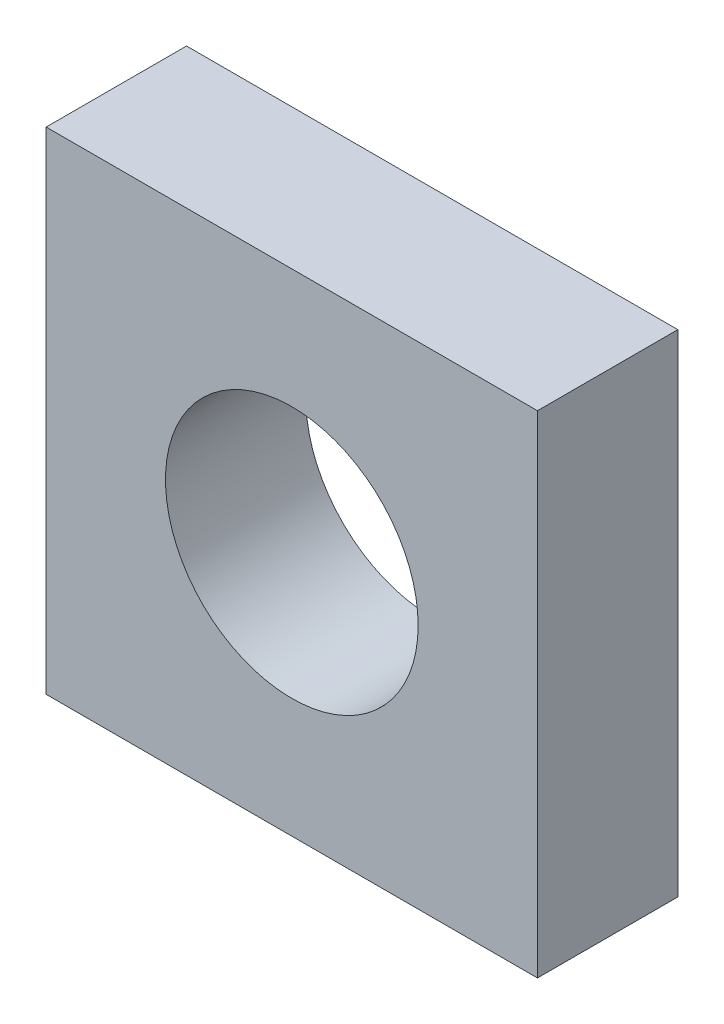
SolidWorks part; units mm, degrees
ref_plane "Plan de face" through (0, 0, 0) normal (0, 0, 1) x (1, 0, 0)
ref_plane "Plan de dessus" through (0, 0, 0) normal (0, 1, 0) x (1, 0, 0)
ref_plane "Plan de droite" through (0, 0, 0) normal (1, 0, 0) x (0, 0, -1)
sketch "Esquisse1" plane through (0, 0, 0) normal (0, 0, 1) x (1, 0, 0)
  line L1 (-35, -35) -> (35, -35)
  line L2 (-35, -35) -> (-35, 35)
  line L3 (-35, 35) -> (35, 35)
  line L4 (35, -35) -> (35, 35)
  line L5 (-35, -35) -> (35, 35) construction
  line L6 (-35, 35) -> (35, -35) construction
  circle A0 centre (0, 0) radius 18
  point P0 (0, 0)
  dimension "D2" = 36
  dimension "D1" = 70
  dimension "D3" = 70
extrude "Boss.-Extru.1" add sketch "Esquisse1" along normal blind 20
